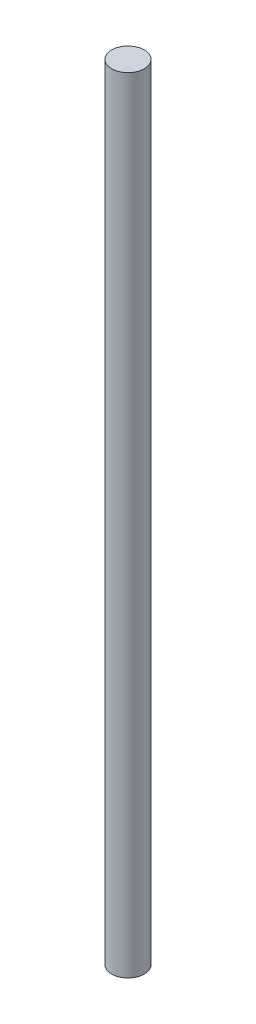
SolidWorks part; units mm, degrees
ref_plane "Front Plane" through (0, 0, 0) normal (0, 0, 1) x (1, 0, 0)
ref_plane "Top Plane" through (0, 0, 0) normal (0, 1, 0) x (1, 0, 0)
ref_plane "Right Plane" through (0, 0, 0) normal (1, 0, 0) x (0, 0, -1)
sketch "Sketch1" plane through (0, 0, 0) normal (0, 1, 0) x (1, 0, 0)
  circle A0 centre (0, 0) radius 9.525
extrude "Boss-Extrude1" add sketch "Sketch1" along normal blind 457.2
